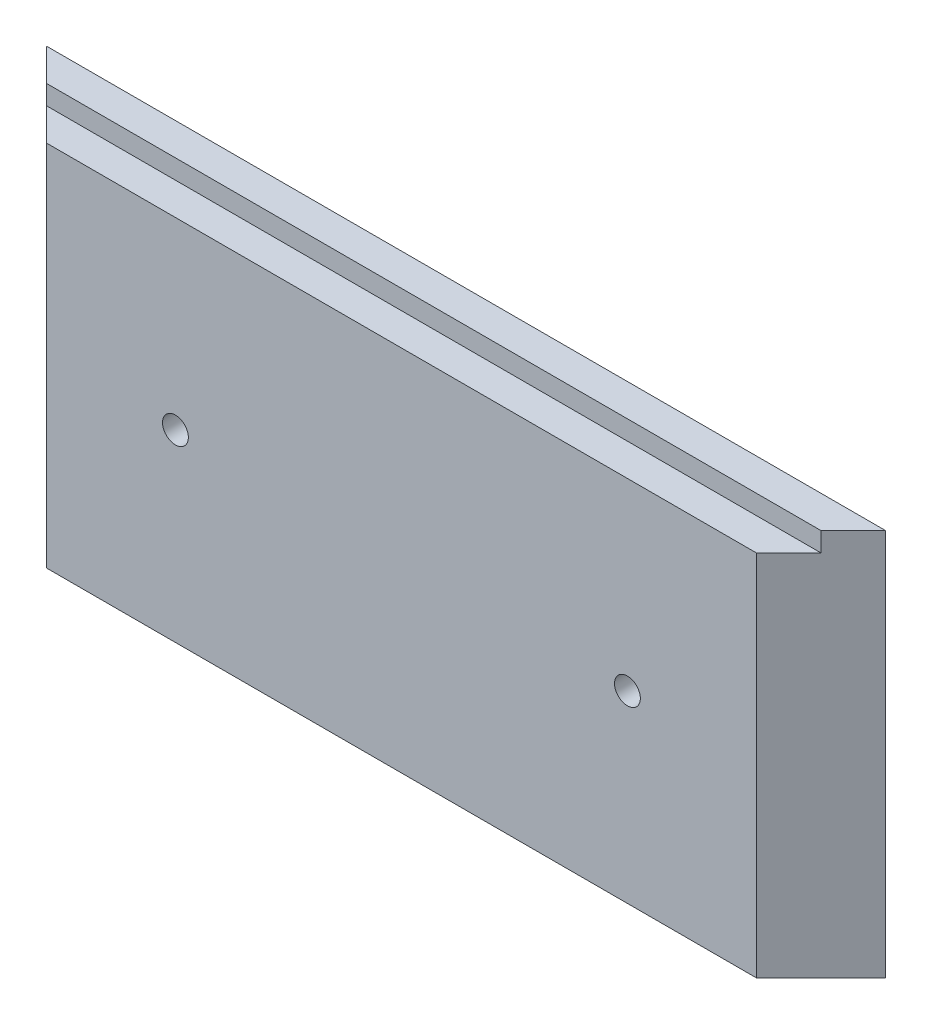
SolidWorks part; units mm, degrees
ref_plane "Front Plane" through (0, 0, 0) normal (0, 0, 1) x (1, 0, 0)
ref_plane "Top Plane" through (0, 0, 0) normal (0, 1, 0) x (1, 0, 0)
ref_plane "Right Plane" through (0, 0, 0) normal (1, 0, 0) x (0, 0, -1)
sketch "Sketch1" plane through (0, 0, 0) normal (0, 1, 0) x (1, 0, 0)
  line L0 (0, 10) -> (10, 0)
  line L1 (0, 0) -> (130, 0)
  line L2 (0, 0) -> (0, 10)
  line L3 (0, 10) -> (130, 10)
  line L4 (130, 0) -> (130, 10)
  line L5 (130, 10) -> (120, 0)
  dimension "D1" = 10
  dimension "D2" = 130
  dimension "D3" = 10
  dimension "D4" = 10
extrude "Boss-Extrude1" add sketch "Sketch1" along normal blind 60 contours L5 L3 L0 L1
sketch "Sketch2" plane through (0, 60, 0) normal (0, 1, 0) x (1, 0, 0)
  line L0 (5, 5) -> (125, 5)
  line L1 (0, 10) -> (10, 0) construction
  line L2 (130, 10) -> (120, 0) construction
  line M2 (120, 0) -> (130, 10)
  line M4 (0, 10) -> (10, 0)
  line M5 (10, 0) -> (120, 0)
extrude "Cut-Extrude1" cut sketch "Sketch2" against normal blind 3 and the other way through all contours L0 M4 M5 M2
sketch "Sketch3" plane through (0, 0, 0) normal (0, 0, 1) x (1, 0, 0)
  line L0 (10, 57) -> (10, 0) construction
  line L1 (120, 57) -> (120, 0) construction
  line L2 (5, 57) -> (125, 57) construction
  line L3 (10, 57) -> (120, 57) construction
  circle A0 centre (30, 28.5) radius 2
  circle A1 centre (100, 28.5) radius 2
  dimension "D1" = 4
  dimension "D2" = 4
  dimension "D3" = 20
  dimension "D4" = 20
  dimension "D5" = 28.5
  dimension "D6" = 28.5
extrude "Cut-Extrude2" cut sketch "Sketch3" against normal blind 4
